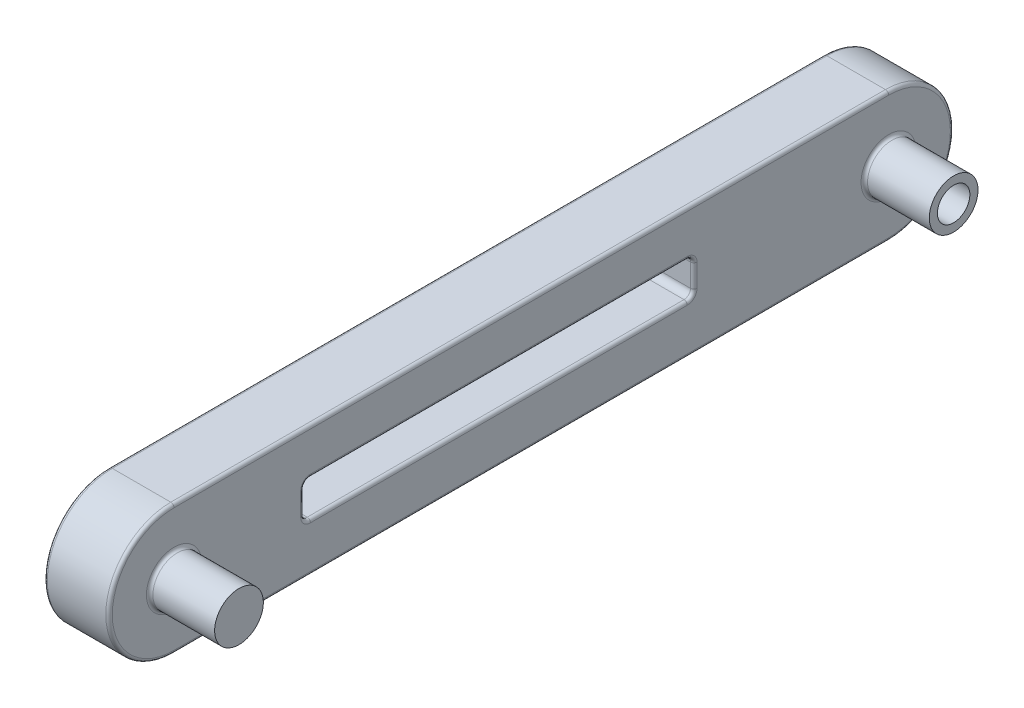
SolidWorks part; units mm, degrees
ref_plane "前视基准面" through (0, 0, 0) normal (0, 0, 1) x (1, 0, 0)
ref_plane "上视基准面" through (0, 0, 0) normal (0, 1, 0) x (1, 0, 0)
ref_plane "右视基准面" through (0, 0, 0) normal (1, 0, 0) x (0, 0, -1)
other "Configuration Table"
sketch "草图1" plane through (0, 0, 0) normal (1, 0, 0) x (0, 0, -1)
  line L0 (0, 0) -> (110, 0) construction
  line L1 (0, 10) -> (110, 10)
  line L2 (0, -10) -> (110, -10)
  arc A0 (0, 10) -> (0, -10) centre (0, 0) ccw
  arc A1 (110, -10) -> (110, 10) centre (110, 0) ccw
  circle A2 centre (0, 0) radius 3.75
  circle A3 centre (110, 0) radius 3.75
  point P3 (55, 0)
  dimension "D2" = 10
  dimension "D3" = 7.5
  dimension "D4" = 7.5
  dimension "D1" = 110
extrude "凸台-拉伸1" add sketch "草图1" along normal blind 10
sketch "草图2" plane through (10, 0, 0) normal (1, 0, 0) x (0, 0, -1)
  circle A0 centre (110, 0) radius 3.75 construction
  circle A1 centre (0, 0) radius 3.75 construction
  circle A2 centre (110, 0) radius 3.75
  circle A3 centre (0, 0) radius 3.75
extrude "凸台-拉伸2" add sketch "草图2" along normal mid plane 20
sketch "草图3" plane through (0, 0, 0) normal (-1, 0, 0) x (0, 0, 1)
  circle A0 centre (-110, 0) radius 2.5 construction
  circle A1 centre (-110, 0) radius 2.5
extrude "切除-拉伸1" cut sketch "草图3" against normal through all
sketch "草图4" plane through (0, 0, 0) normal (-1, 0, 0) x (0, 0, 1)
  line L0 (-80, 3) -> (-20, 3)
  line L1 (-20, 3) -> (-20, -2.5)
  line L2 (-20, -2.5) -> (-80, -2.5)
  line L3 (-80, -2.5) -> (-80, 3)
  line L4 (0, 10) -> (0, -10)
  line L5 (-110, 10) -> (0, 10) construction
  dimension "D1" = 20
  dimension "D2" = 7
  dimension "D3" = 5.5
  dimension "D4" = 60
extrude "切除-拉伸2" cut sketch "草图4" against normal blind 10 contours L3 L2 L1 L0
fillet "圆角1" radius 1 4 edges at (5, -2.5, -20) (5, 3, -20) (5, 3, -80) (5, -2.5, -80)
fillet "圆角2" radius 0.5 27 edges at (10, 2.7071, -20.2929) (10, 0.25, -20) (10, -2.2071, -20.2929) (10, -2.5, -50) (10, -2.2071, -79.7071) (10, 0.25, -80) (10, 2.7071, -79.7071) (10, 3, -50) (10, 0, -113.75) (10, 10, -55) (10, 0, -120) (10, -10, -55) (10, 0, 10) (10, 0, -3.75) (0, -2.2071, -20.2929) (0, 0.25, -20) (0, 2.7071, -20.2929) (0, 3, -50) (0, 2.7071, -79.7071) (0, 0.25, -80) (0, -2.2071, -79.7071) (0, -2.5, -50) (0, 0, -107.5) (0, -10, -55) (0, 0, -120) (0, 10, -55) (0, 0, 10)
